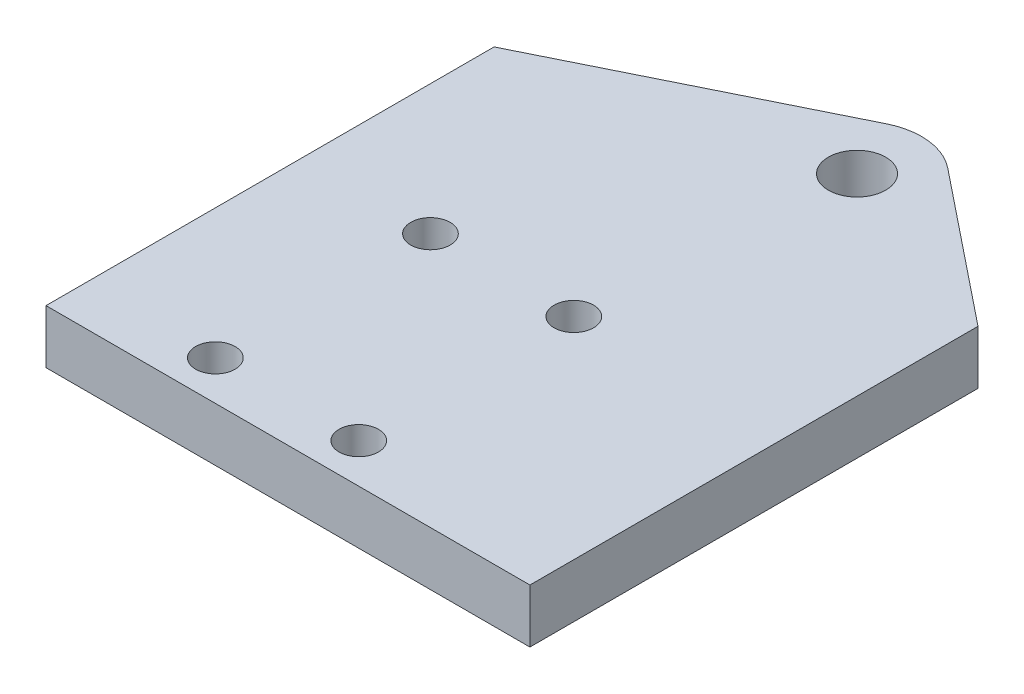
SolidWorks part; units mm, degrees
ref_plane "前视基准面" through (0, 0, 0) normal (0, 0, 1) x (1, 0, 0)
ref_plane "上视基准面" through (0, 0, 0) normal (0, 1, 0) x (1, 0, 0)
ref_plane "右视基准面" through (0, 0, 0) normal (1, 0, 0) x (0, 0, -1)
sketch "草图2" plane through (0, 0, 0) normal (0, 1, 0) x (1, 0, 0)
  line L0 (11.25, 26.9) -> (11.25, -12.1287) construction
  line L1 (0, 0) -> (27, 0)
  line L2 (0, 0) -> (0, 25)
  line L4 (27, 0) -> (27, 25)
  line L5 (3.75, 8.2) -> (23.25, 8.2) construction
  line L6 (0, 25) -> (14.6577, 32.2287)
  line L7 (27, 25) -> (18.501, 31.8095)
  circle A0 centre (7.25, 14.2) radius 1.1
  circle A1 centre (15.25, 14.2) radius 1.1
  circle A2 centre (15.25, 2.2) radius 1.1
  circle A3 centre (7.25, 2.2) radius 1.1
  circle A4 centre (16.25, 29) radius 1.6
  arc A5 (18.501, 31.8095) -> (14.6577, 32.2287) centre (16.25, 29) ccw
  dimension "D3" = 2.2
  dimension "D4" = 8
  dimension "D5" = 12
  dimension "D7" = 3.2
  dimension "D8" = 2
  dimension "D9" = 27
  dimension "D10" = 5
  dimension "D6" = 2.2
  dimension "D1" = 29
  dimension "D2" = 25
  dimension "D11" = 11.25
extrude "凸台-拉伸1" add sketch "草图2" along normal blind 3
sketch "草图3" plane through (0, 0, 0) normal (0, -1, 0) x (1, 0, 0)
  line L2 (27, -25) -> (18.501, -31.8095) construction
  line L3 (19.7441, -30.8135) -> (18.501, -31.8095)
  line L4 (14.6577, -32.2287) -> (0, -25) construction
  line L5 (14.6577, -32.2287) -> (1.7441, -25.8601)
  line L8 (16.25, -18) -> (16.25, -40.2215) construction
  line L9 (1.7441, -25.8601) -> (1.7441, -18)
  line L10 (1.7441, -18) -> (19.7441, -18)
  line L11 (19.7441, -18) -> (19.7441, -30.8135)
  line L12 (0, 0) -> (27, 0) construction
  circle A0 centre (16.25, -29) radius 1.6
  arc A2 (14.6577, -32.2287) -> (18.501, -31.8095) centre (16.25, -29) ccw construction
  arc A3 (14.6577, -32.2287) -> (18.501, -31.8095) centre (16.25, -29) ccw
  circle A4 centre (16.25, -29) radius 1.6 construction
  dimension "D1" = 18
  dimension "D2" = 18
extrude "凸台-拉伸2" add sketch "草图3" along normal blind 3
